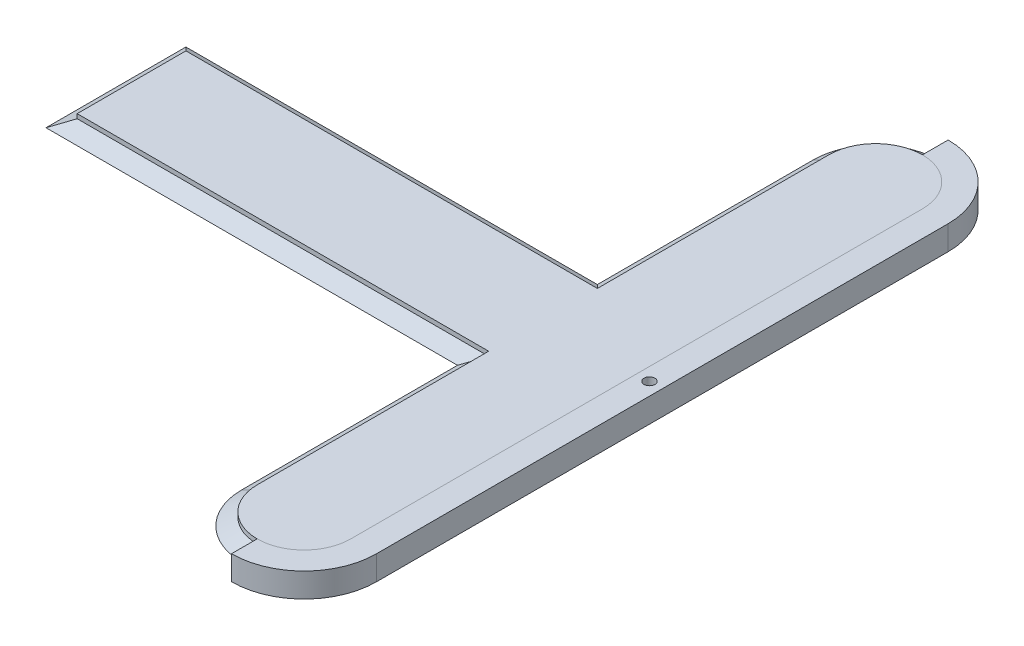
SolidWorks part; units mm, degrees
ref_plane "Front Plane" through (0, 0, 0) normal (0, 0, 1) x (1, 0, 0)
ref_plane "Top Plane" through (0, 0, 0) normal (0, 1, 0) x (1, 0, 0)
ref_plane "Right Plane" through (0, 0, 0) normal (1, 0, 0) x (0, 0, -1)
sketch "Sketch1" plane through (0, 0, 0) normal (0, 1, 0) x (1, 0, 0)
  line L0 (0, -13.4216) -> (101.6, -13.4216)
  line L1 (101.6, -13.4216) -> (101.6, -70.5716)
  line L2 (124.714, -70.5716) -> (124.714, 70.5716)
  line L3 (101.6, 70.5716) -> (101.6, 13.4216)
  line L4 (101.6, 13.4216) -> (0, 13.4216)
  line L5 (0, 13.4216) -> (0, -13.4216)
  arc A0 (101.6, -70.5716) -> (124.714, -70.5716) centre (113.157, -70.5716) ccw
  arc A1 (124.714, 70.5716) -> (101.6, 70.5716) centre (113.157, 70.5716) ccw
  point P12 (0, 0)
extrude "Boss-Extrude1" add sketch "Sketch1" along normal blind 6
sketch "Sketch2" plane through (0, 0, 0) normal (0, 0, 1) x (1, 0, 0)
  line L0 (0, 3) -> (101.6, 3)
  line L1 (0, 6) -> (0, 0) construction
  line L2 (101.6, 6) -> (101.6, 0) construction
split line "Split Line1"
sketch "Sketch3" plane through (0, 0, 0) normal (1, 0, 0) x (0, 0, -1)
  line L0 (82.1286, 3) -> (-82.1286, 3)
  line L1 (82.1286, 0) -> (82.1286, 6) construction
  line L2 (-82.1286, 6) -> (-82.1286, 0) construction
split line "Split Line2"
curve "CompCurve1"
ref_plane "Plane1" through (113.157, 0, 0) normal (1, 0, 0) x (0, 0, -1)
sketch "Sketch4" plane through (113.157, 0, 0) normal (1, 0, 0) x (0, 0, -1)
  line L0 (82.1286, 4.9103) -> (82.1286, 1.0603)
  line L6 (82.1286, 3) -> (82.1286, 6) construction
  line L7 (82.1286, 0) -> (82.1286, 3) construction
  line L8 (82.1286, 4.9103) -> (85.9786, 2.9853)
  line L9 (82.1286, 1.0603) -> (85.9786, 2.9853)
  dimension "D1" = 3.85
  dimension "D2" = 3.85
sweep "Sweep1" add profiles "Sketch4" path "CompCurve1"
sketch "Sketch5" plane through (0, 6, 0) normal (0, 1, 0) x (1, 0, 0)
  line L0 (131.064, -70.5716) -> (131.064, 70.5716)
  line L1 (113.157, 88.4786) -> (113.157, 82.1286)
  line L2 (124.714, 70.5716) -> (124.714, -70.5716)
  line L3 (113.157, -82.1286) -> (113.157, -88.4786)
  line L4 (113.157, -82.1286) -> (113.157, -79.7009) construction
  line L5 (113.157, 82.1286) -> (113.157, 81.4216) construction
  line L6 (113.157, -3.3) -> (113.157, 3.3) construction
  arc A0 (131.064, 70.5716) -> (113.157, 88.4786) centre (113.157, 70.5716) ccw
  arc A1 (124.714, 70.5716) -> (113.157, 82.1286) centre (113.157, 70.5716) ccw
  arc A2 (113.157, -82.1286) -> (124.714, -70.5716) centre (113.157, -70.5716) ccw
  arc A3 (113.157, -88.4786) -> (131.064, -70.5716) centre (113.157, -70.5716) ccw
  arc A4 (124.714, 70.5716) -> (101.6, 70.5716) centre (113.157, 70.5716) ccw construction
  arc A5 (101.6, -70.5716) -> (124.714, -70.5716) centre (113.157, -70.5716) ccw construction
  dimension "D1" = 6.35
extrude "Boss-Extrude2" add sketch "Sketch5" along a picked direction on the side against the normal up to surface (6 mm away) separate body
sketch "Sketch6" plane through (0, 6, 0) normal (0, 1, 0) x (1, 0, 0)
  line L0 (0, 0) -> (131.064, 0) construction
  line L1 (131.064, -70.5716) -> (131.064, 70.5716) construction
  line L2 (124.714, 0) -> (131.064, 0) construction
  line L3 (124.714, -70.5716) -> (124.714, 70.5716) construction
  circle A0 centre (127.889, 0) radius 1.35
  dimension "D1" = 2.7
extrude "Cut-Extrude1" cut sketch "Sketch6" against normal blind 17.78
